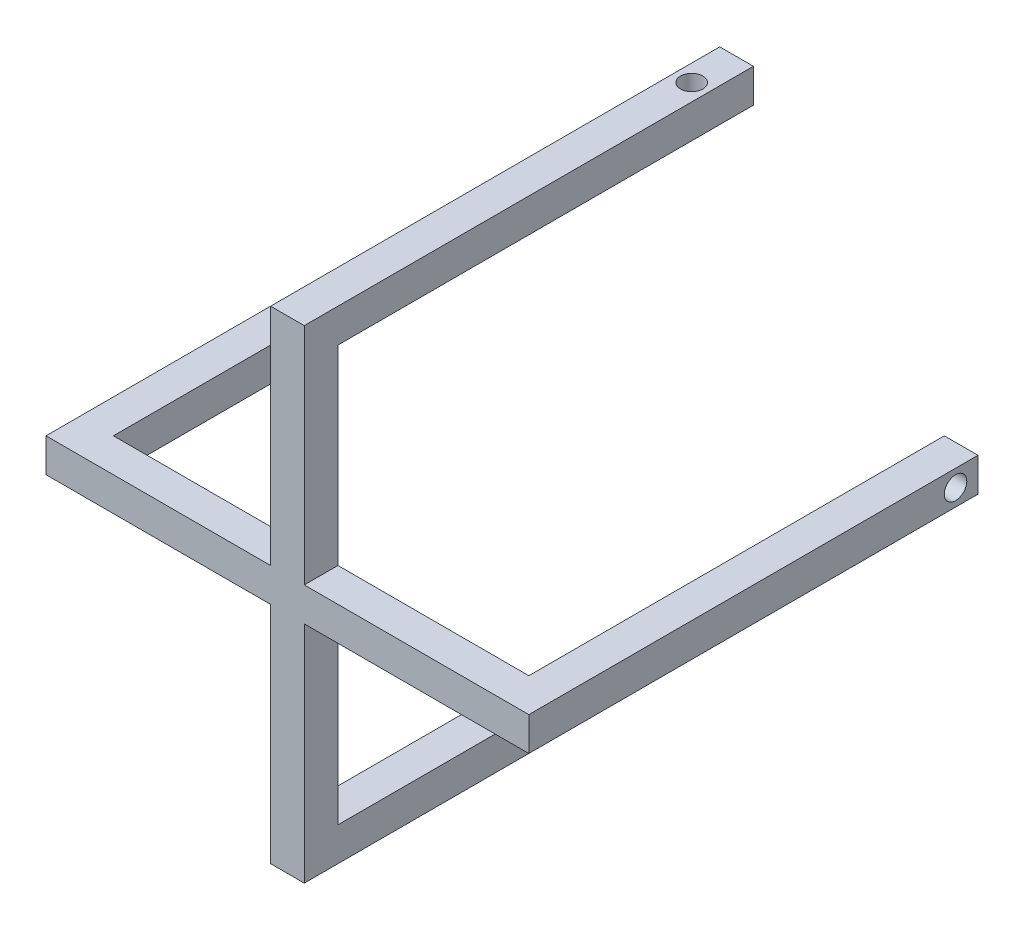
SolidWorks part; units mm, degrees
material "1060 Alloy"
ref_plane "Front Plane" through (0, 0, 0) normal (0, 0, 1) x (1, 0, 0)
ref_plane "Top Plane" through (0, 0, 0) normal (0, 1, 0) x (1, 0, 0)
ref_plane "Right Plane" through (0, 0, 0) normal (1, 0, 0) x (0, 0, -1)
sketch "Sketch1" plane through (0, 0, 0) normal (0, 0, 1) x (1, 0, 0)
  line L0 (92.5, -7.5) -> (107.5, -7.5)
  line L1 (-7.5, 92.5) -> (7.5, 92.5)
  line L2 (-7.5, 92.5) -> (-7.5, 107.5)
  line L3 (-7.5, 107.5) -> (7.5, 107.5)
  line L4 (7.5, 92.5) -> (7.5, 107.5)
  line L5 (-7.5, 92.5) -> (7.5, 107.5) construction
  line L6 (-7.5, 107.5) -> (7.5, 92.5) construction
  line L7 (107.5, 7.5) -> (107.5, -7.5)
  line L8 (92.5, 7.5) -> (107.5, 7.5)
  line L9 (92.5, 7.5) -> (92.5, -7.5)
  line L10 (-7.5, -92.5) -> (-7.5, -107.5)
  line L11 (7.5, -107.5) -> (-7.5, -107.5)
  line L12 (7.5, -92.5) -> (7.5, -107.5)
  line L13 (7.5, -92.5) -> (-7.5, -92.5)
  line L14 (-92.5, 7.5) -> (-107.5, 7.5)
  line L15 (-107.5, -7.5) -> (-107.5, 7.5)
  line L16 (-92.5, -7.5) -> (-107.5, -7.5)
  line L17 (-92.5, -7.5) -> (-92.5, 7.5)
  circle A0 centre (0, 0) radius 100
  point P3 (0, 100)
  point P23 (0, 0)
  dimension "D1" = 200
  dimension "D2" = 15
  dimension "D3" = 15
  dimension "D4" = 4
extrude "Boss-Extrude2" add sketch "Sketch1" along normal blind 200 contours A0 L4 L3 L2 | L4 A0 L2 L1 | L14 A0 L16 L17 | A0 L14 L15 L16 | L10 A0 L12 L13 | A0 L10 L11 L12 | L7 L0 L9 L8
sketch "Sketch2" plane through (0, -107.5, 0) normal (0, -1, 0) x (1, 0, 0)
  line L0 (-7.5, 200) -> (-7.5, 0) construction
  line L1 (7.5, 200) -> (-7.5, 200)
  line L2 (7.5, 200) -> (7.5, 185)
  line L3 (7.5, 185) -> (-7.5, 185)
  line L4 (-7.5, 200) -> (-7.5, 185)
  dimension "D1" = 15
extrude "Boss-Extrude3" add sketch "Sketch2" against normal up to surface (215 mm away) up to face at (0, 107.5, 100)
sketch "Sketch3" plane through (107.5, 0, 0) normal (1, 0, 0) x (0, 0, -1)
  line L0 (-185, 92.5) -> (-185, -92.5) construction
  line L1 (-200, 7.5) -> (-185, 7.5)
  line L2 (-200, 7.5) -> (-200, -7.5)
  line L3 (-200, -7.5) -> (-185, -7.5)
  line L4 (-185, 7.5) -> (-185, -7.5)
  line L5 (-200, -7.5) -> (0, -7.5) construction
extrude "Boss-Extrude4" add sketch "Sketch3" against normal up to surface (215 mm away) up to face at (-107.5, 0, 100)
sketch "Sketch4" plane through (107.5, 0, 0) normal (1, 0, 0) x (0, 0, -1)
  circle A0 centre (-10, 0) radius 5
  dimension "D1" = 10
  dimension "D2" = 10
extrude "Cut-Extrude1" cut sketch "Sketch4" against normal through all
sketch "Sketch5" plane through (0, -107.5, 0) normal (0, -1, 0) x (1, 0, 0)
  circle A0 centre (0, 20) radius 5
  dimension "D1" = 10
  dimension "D2" = 20
extrude "Cut-Extrude3" cut sketch "Sketch5" against normal through all contours A0
